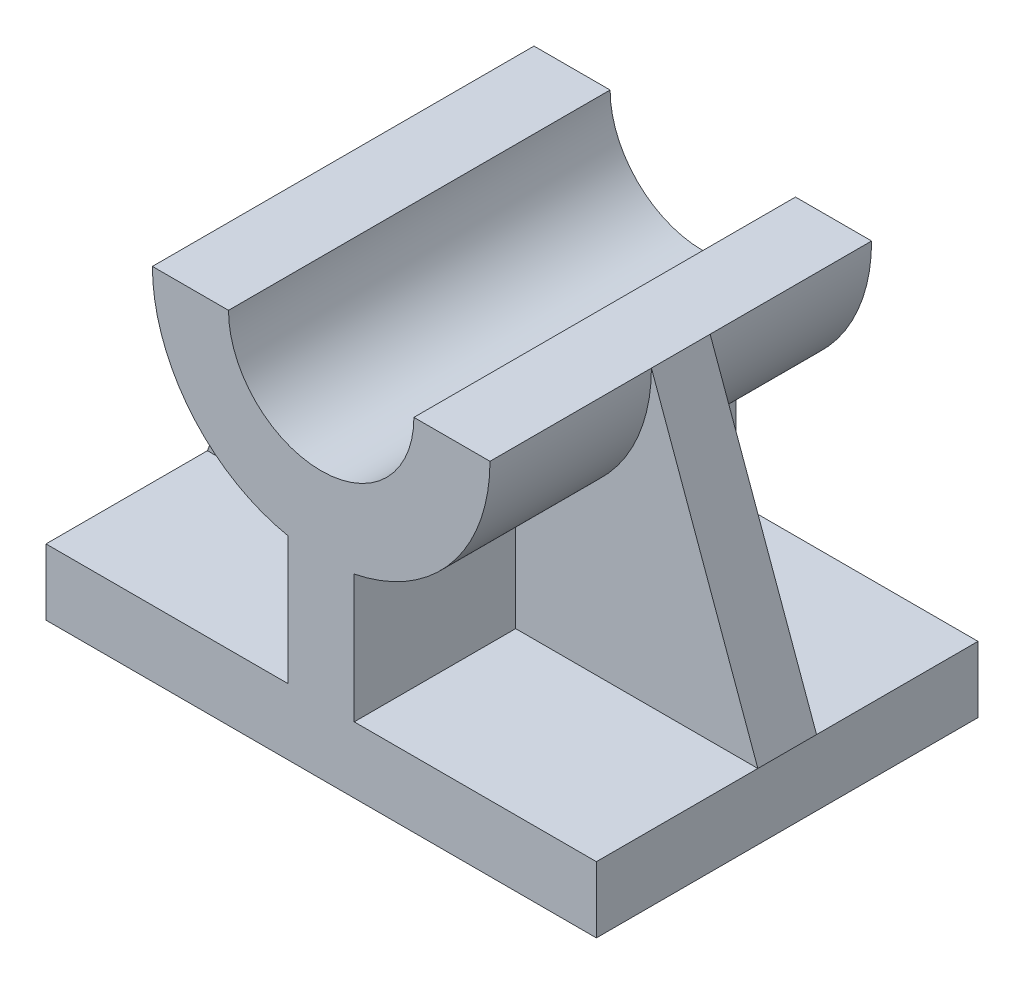
SolidWorks part; units mm, degrees
material "Ti-8Al-1Mo-1V annealed sheet (SS)"
ref_plane "Front Plane" through (0, 0, 0) normal (0, 0, 1) x (1, 0, 0)
ref_plane "Top Plane" through (0, 0, 0) normal (0, 1, 0) x (1, 0, 0)
ref_plane "Right Plane" through (0, 0, 0) normal (1, 0, 0) x (0, 0, -1)
sketch "Sketch11" plane through (0, 0, 0) normal (0, 0, 1) x (1, 0, 0)
  line L0 (23000, 44500) -> (12632.3716, 44500)
  line L1 (-37500, 4500) -> (-4500, 4500)
  line L2 (-37500, 4500) -> (-37500, -4500)
  line L3 (-37500, -4500) -> (37500, -4500)
  line L4 (37500, 4500) -> (37500, -4500)
  line L5 (-37500, 4500) -> (37500, -4500) construction
  line L6 (-37500, -4500) -> (37500, 4500) construction
  line L7 (-12632.3716, 44500) -> (-23000, 44500)
  line L8 (-4500, 21944.5129) -> (-4500, 4500)
  line L9 (0, 44500) -> (0, -4500) construction
  line L10 (4500, 21944.5129) -> (4500, 4500)
  line L11 (4500, 4500) -> (37500, 4500)
  arc A0 (-23000, 44500) -> (-4500, 21944.5129) centre (0, 44500) ccw
  arc A1 (-12632.3716, 44500) -> (12632.3716, 44500) centre (0, 44500) ccw
  arc A2 (4500, 21944.5129) -> (23000, 44500) centre (0, 44500) ccw
  point P0 (0, 0)
  dimension "D3" = 46000
  dimension "D4" = 25264.7433
  dimension "D1" = 9000
  dimension "D2" = 75000
  dimension "D5" = 40000
  dimension "D6" = 4500
extrude "Boss-Extrude5" add sketch "Sketch11" along normal mid plane 52000
sketch "Sketch14" plane through (0, 0, 0) normal (0, 0, 1) x (1, 0, 0)
  line L0 (23000, 44500) -> (37500, 4500)
rib "Rib7" sketch "Sketch14" sketch "Sketch14" thickness 8000 extrusion direction parallel to sketch draft on no parameters "D1"=8000
mirror "Mirror1" about plane through (0, 0, 0) normal (1, 0, 0) of "Rib7"
